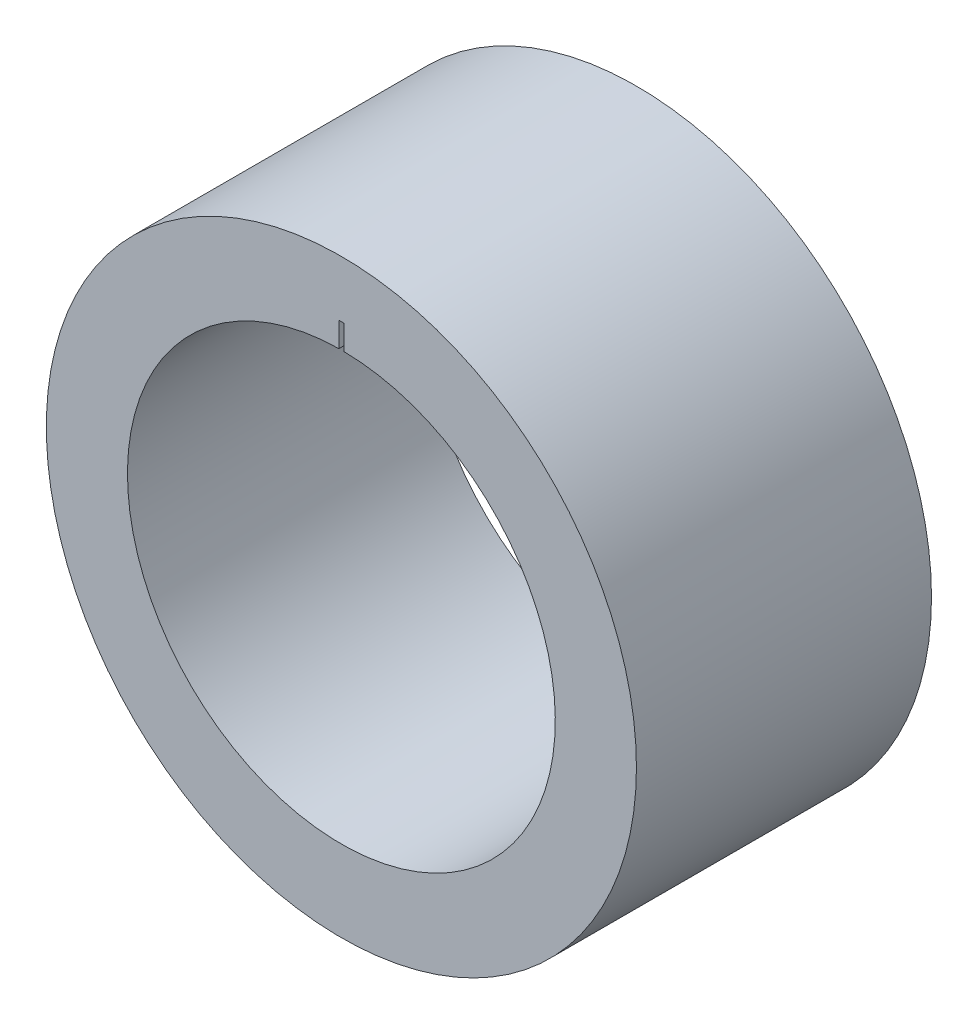
SolidWorks part; units mm, degrees
ref_plane "Front Plane" through (0, 0, 0) normal (0, 0, 1) x (1, 0, 0)
ref_plane "Top Plane" through (0, 0, 0) normal (0, 1, 0) x (1, 0, 0)
ref_plane "Right Plane" through (0, 0, 0) normal (1, 0, 0) x (0, 0, -1)
ref_plane "Plane1"
sketch "Sketch1" plane through (0, 0, 0) normal (0, 0, 1) x (1, 0, 0)
  circle A0 centre (0, 0) radius 60
  circle A1 centre (0, 0) radius 43.5
  dimension "D1" = 87
  dimension "D2" = 120
extrude "Extrusion1" add sketch "Sketch1" along normal blind 60 contours A0 A1
ref_plane "Plane2"
ref_plane "Plane3"
sketch "Sketch3" plane through (0, 0, 60) normal (0, 0, 1) x (1, 0, 0)
  line L0 (-0.5, 48.5) -> (-0.5, 43.4971)
  line L1 (0.5, 43.4971) -> (0.5, 48.5)
  line L2 (0.5, 48.5) -> (-0.5, 48.5)
  arc A0 (0.5, 43.4971) -> (-0.5, 43.4971) centre (0, 0) ccw
extrude "Extrusion3" cut sketch "Sketch3" against normal blind 60
